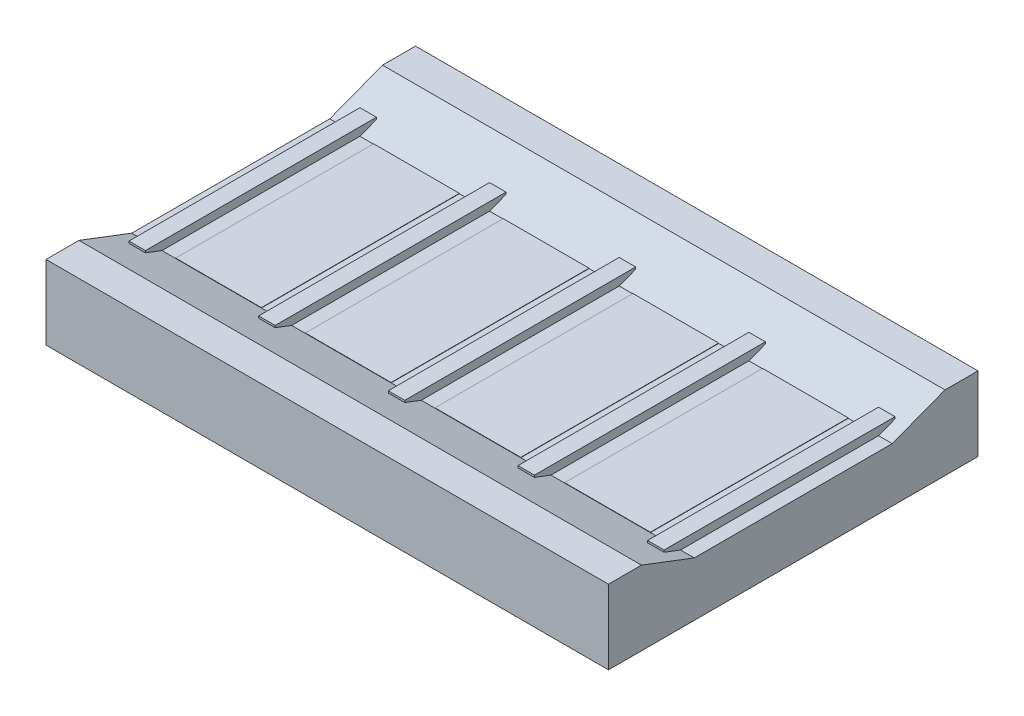
SolidWorks part; units mm, degrees
ref_plane "Front" through (0, 0, 0) normal (0, 0, 1) x (1, 0, 0)
ref_plane "Top" through (0, 0, 0) normal (0, 1, 0) x (1, 0, 0)
ref_plane "Right" through (0, 0, 0) normal (1, 0, 0) x (0, 0, -1)
sketch "Sketch1" plane through (0, 0, 0) normal (1, 0, 0) x (0, 0, -1)
  line L0 (-3, 0.515) -> (3, 0.515)
  line L1 (-5.6, -1.125) -> (5.6, -1.125)
  line L2 (-5.6, -1.125) -> (-5.6, 1.125)
  line L3 (-5.6, 1.125) -> (-4.6, 1.125)
  line L4 (5.6, -1.125) -> (5.6, 1.125)
  line L5 (-5.6, -1.125) -> (5.6, 1.125) construction
  line L6 (-5.6, 1.125) -> (5.6, -1.125) construction
  line L7 (-3, 0.515) -> (-4.6, 1.125)
  line L8 (0, 2.4649) -> (0, -2.0521) construction
  line L9 (-4.99, 0.515) -> (4.99, 0.515) construction
  line L10 (-4.99, -0.515) -> (4.99, -0.515) construction
  line L11 (-4.99, -0.515) -> (-4.99, 0.515) construction
  line L12 (4.99, -0.515) -> (4.99, 0.515) construction
  line L13 (3, 0.515) -> (4.6, 1.125)
  line L14 (4.6, 1.125) -> (5.6, 1.125)
  line L15 (-5.6, 1.125) -> (5.6, 1.125) construction
  point P0 (0, 0)
  dimension "D1" = 11.2
  dimension "D2" = 2.25
  dimension "D4" = 6
  dimension "D5" = 1
  dimension "D3" = 0.61
extrude "Boss-Extrude1" add sketch "Sketch1" along normal mid plane 17.05
sketch "Sketch2" plane through (0, 0.515, 0) normal (0, 1, 0) x (1, 0, 0)
  line L0 (-8.11, 3.5) -> (-8.11, -3.5)
  line L3 (-8.11, -3.5) -> (-7.61, -3.5)
  line L4 (-7.61, -3.5) -> (-7.61, 3.5)
  line L5 (-8.11, 3.5) -> (-7.61, 3.5)
  line L6 (-9.3505, 0) -> (11.1519, 0) construction
  line L7 (-8.525, 3) -> (-8.525, -3) construction
  line L8 (-4.18, 3.5) -> (-4.18, -3.5)
  line L9 (-4.18, -3.5) -> (-3.68, -3.5)
  line L10 (-3.68, -3.5) -> (-3.68, 3.5)
  line L11 (-4.18, 3.5) -> (-3.68, 3.5)
  line L12 (-0.25, 3.5) -> (-0.25, -3.5)
  line L13 (-0.25, -3.5) -> (0.25, -3.5)
  line L14 (0.25, -3.5) -> (0.25, 3.5)
  line L15 (-0.25, 3.5) -> (0.25, 3.5)
  line L16 (3.68, 3.5) -> (3.68, -3.5)
  line L17 (3.68, -3.5) -> (4.18, -3.5)
  line L18 (4.18, -3.5) -> (4.18, 3.5)
  line L19 (3.68, 3.5) -> (4.18, 3.5)
  line L20 (7.61, 3.5) -> (7.61, -3.5)
  line L21 (7.61, -3.5) -> (8.11, -3.5)
  line L22 (8.11, -3.5) -> (8.11, 3.5)
  line L23 (7.61, 3.5) -> (8.11, 3.5)
  dimension "D1" = 7
  dimension "D2" = 0.5
  dimension "D3" = 0.415
  dimension "D4" = 5
extrude "Boss-Extrude2" add sketch "Sketch2" along normal blind 0.25
sketch "Sketch3" plane through (0, 0.515, 0) normal (0, 1, 0) x (1, 0, 0)
  line L0 (-5.895, 3) -> (-5.895, -3) construction
  line L1 (-4.595, -3) -> (-7.195, -3)
  line L2 (-4.595, -3) -> (-4.595, 3)
  line L3 (-4.595, 3) -> (-7.195, 3)
  line L4 (-7.195, -3) -> (-7.195, 3)
  line L5 (-4.595, -3) -> (-7.195, 3) construction
  line L6 (-4.595, 3) -> (-7.195, -3) construction
  line L7 (-4.18, 3) -> (-7.61, 3) construction
  line L8 (-4.18, -3) -> (-7.61, -3) construction
  line L9 (9.6393, 0) -> (-10.23, 0) construction
  line L10 (-0.665, -3) -> (-3.265, -3)
  line L12 (-0.665, -3) -> (-0.665, 3)
  line L13 (-0.665, 3) -> (-3.265, 3)
  line L14 (-3.265, -3) -> (-3.265, 3)
  line L15 (-1.965, 3) -> (-1.965, -3) construction
  line L16 (-0.665, -3) -> (-3.265, 3) construction
  line L17 (-0.665, 3) -> (-3.265, -3) construction
  line L18 (3.265, -3) -> (0.665, -3)
  line L19 (3.265, -3) -> (3.265, 3)
  line L20 (3.265, 3) -> (0.665, 3)
  line L21 (0.665, -3) -> (0.665, 3)
  line L22 (1.965, 3) -> (1.965, -3) construction
  line L23 (3.265, -3) -> (0.665, 3) construction
  line L24 (3.265, 3) -> (0.665, -3) construction
  line L25 (7.195, -3) -> (4.595, -3)
  line L26 (7.195, -3) -> (7.195, 3)
  line L27 (7.195, 3) -> (4.595, 3)
  line L28 (4.595, -3) -> (4.595, 3)
  line L29 (5.895, 3) -> (5.895, -3) construction
  line L30 (7.195, -3) -> (4.595, 3) construction
  line L31 (7.195, 3) -> (4.595, -3) construction
  line L32 (-5.895, 0) -> (-1.965, 0) construction
  point P0 (-5.895, 0)
  point P15 (-1.965, 0)
  point P22 (1.965, 0)
  point P29 (5.895, 0)
  dimension "D1" = 2.6
  dimension "D2" = 4
  dimension "D3" = 3.93
extrude "Boss-Extrude3" add sketch "Sketch3" along normal blind 0.01
